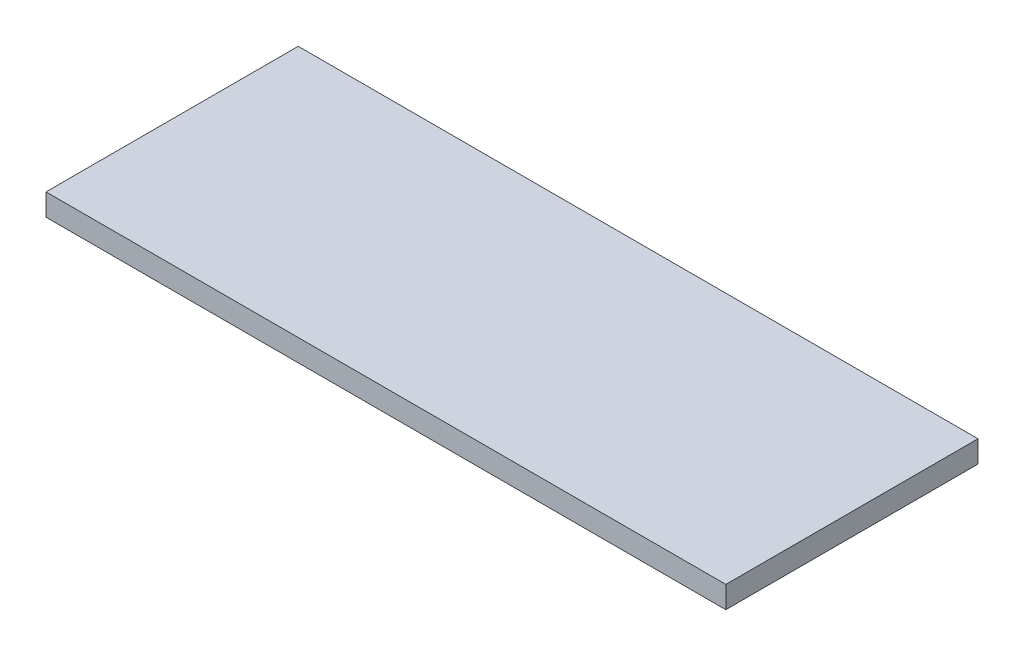
SolidWorks part; units mm, degrees
ref_plane "Front Plane" through (0, 0, 0) normal (0, 0, 1) x (1, 0, 0)
ref_plane "Top Plane" through (0, 0, 0) normal (0, 1, 0) x (1, 0, 0)
ref_plane "Right Plane" through (0, 0, 0) normal (1, 0, 0) x (0, 0, -1)
sketch "Sketch1" plane through (0, 0, 0) normal (0, 1, 0) x (1, 0, 0)
  line L1 (0, 0) -> (310, 0)
  line L2 (0, 0) -> (0, 115)
  line L3 (0, 115) -> (310, 115)
  line L4 (310, 0) -> (310, 115)
  dimension "D1" = 310
  dimension "D2" = 115
extrude "Boss-Extrude1" add sketch "Sketch1" along normal blind 10
